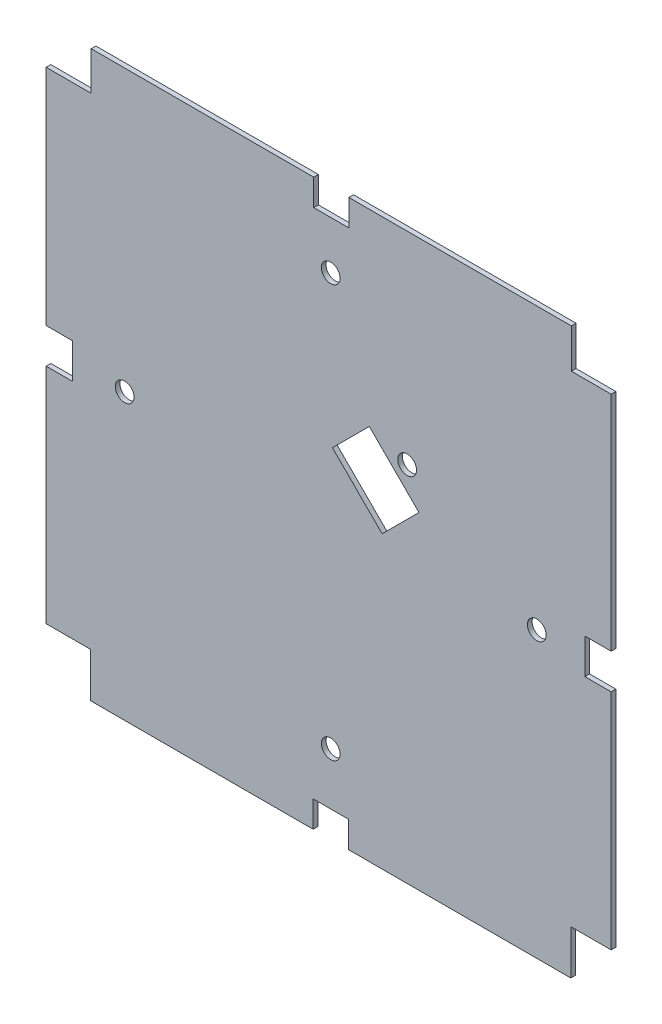
SolidWorks part; units mm, degrees
ref_plane "Front Plane" through (0, 0, 0) normal (0, 0, 1) x (1, 0, 0)
ref_plane "Top Plane" through (0, 0, 0) normal (0, 1, 0) x (1, 0, 0)
ref_plane "Right Plane" through (0, 0, 0) normal (1, 0, 0) x (0, 0, -1)
sketch "Sketch1" plane through (0, 0, 0) normal (0, 0, 1) x (1, 0, 0)
  line L1 (-67.0283, 35.647) -> (29.4717, 35.647)
  line L2 (-67.0283, 35.647) -> (-67.0283, -60.853)
  line L3 (-67.0283, -60.853) -> (29.4717, -60.853)
  line L4 (29.4717, 35.647) -> (29.4717, -60.853)
  line L5 (-67.0283, 35.647) -> (-59.3283, 35.647)
  line L6 (-67.0283, 35.647) -> (-67.0283, 29.047)
  line L7 (-67.0283, 29.047) -> (-59.3283, 29.047)
  line L8 (-59.3283, 35.647) -> (-59.3283, 29.047)
  line L21 (-67.0283, -9.153) -> (-62.5283, -9.153)
  line L22 (-67.0283, -9.153) -> (-67.0283, -15.153)
  line L23 (-67.0283, -15.153) -> (-62.5283, -15.153)
  line L24 (-62.5283, -9.153) -> (-62.5283, -15.153)
  line L25 (29.4717, 35.647) -> (22.6717, 35.647)
  line L26 (29.4717, 35.647) -> (29.4717, 28.947)
  line L27 (29.4717, 28.947) -> (22.6717, 28.947)
  line L28 (22.6717, 35.647) -> (22.6717, 28.947)
  line L29 (29.4717, -15.073) -> (24.9717, -15.073)
  line L30 (29.4717, -15.073) -> (29.4717, -9.073)
  line L31 (29.4717, -9.073) -> (24.9717, -9.073)
  line L32 (24.9717, -15.073) -> (24.9717, -9.073)
  line L33 (29.4717, -60.853) -> (22.5717, -60.853)
  line L34 (29.4717, -60.853) -> (29.4717, -53.253)
  line L35 (29.4717, -53.253) -> (22.5717, -53.253)
  line L36 (22.5717, -60.853) -> (22.5717, -53.253)
  line L37 (-67.0283, -60.853) -> (-59.4283, -60.853)
  line L38 (-67.0283, -60.853) -> (-67.0283, -53.253)
  line L39 (-67.0283, -53.253) -> (-59.4283, -53.253)
  line L40 (-59.4283, -60.853) -> (-59.4283, -53.253)
  line L42 (-21.3283, 35.647) -> (-15.3283, 35.647)
  line L43 (-21.3283, 35.647) -> (-21.3283, 31.147)
  line L44 (-21.3283, 31.147) -> (-15.3283, 31.147)
  line L45 (-15.3283, 35.647) -> (-15.3283, 31.147)
  line L47 (-21.4283, -60.853) -> (-15.4283, -60.853)
  line L48 (-21.4283, -60.853) -> (-21.4283, -56.353)
  line L49 (-21.4283, -56.353) -> (-15.4283, -56.353)
  line L50 (-15.4283, -60.853) -> (-15.4283, -56.353)
  circle A0 centre (16.7687, -12.2528) radius 1.6
  circle A1 centre (-18.4281, 22.944) radius 1.6
  circle A2 centre (-18.4281, -47.4496) radius 1.6
  circle A3 centre (-53.625, -12.2528) radius 1.6
  circle A4 centre (-5.3709, 1.097) radius 1.6
  circle A5 centre (16.7687, -12.2528) radius 1.7 construction
  circle A6 centre (-53.625, -12.2528) radius 1.7 construction
  circle A7 centre (-18.4281, 22.944) radius 1.7 construction
  circle A8 centre (-18.4281, -47.4496) radius 1.7 construction
  circle A10 centre (-5.3709, 1.097) radius 1.6 construction
  dimension "D17" = 3.2
  dimension "D19" = 3.2
  dimension "D20" = 3.2
  dimension "D21" = 3.2
  dimension "D27" = 3.2
  dimension "D16" = 0
  dimension "D22" = 0
  dimension "D23" = 0
  dimension "D1" = 96.5
  dimension "D2" = 96.5
  dimension "D3" = 4.5
  dimension "D4" = 7.7
  dimension "D5" = 6.6
  dimension "D6" = 6
  dimension "D7" = 45.7
  dimension "D8" = 7.6
  dimension "D9" = 7.6
  dimension "D10" = 6.9
  dimension "D11" = 7.6
  dimension "D12" = 6
  dimension "D13" = 4.5
  dimension "D14" = 6.7
  dimension "D15" = 6.8
  dimension "D18" = 0
  dimension "D25" = 0
  dimension "D28" = 4.5
  dimension "D29" = 6
  dimension "D30" = 45.7
  dimension "D33" = 4.5
  dimension "D34" = 6
  dimension "D35" = 45.6
extrude "Boss-Extrude1" add sketch "Sketch1" along normal blind 0.8 contours L40 L3 L36 L35 L4 L29 L32 L31 L27 L28 L1 L8 L7 L2 L21 L24 L23 L39 A4 A3 A2 A1 A0
sketch "Sketch2" plane through (0, 0, 0.8) normal (0, 0, 1) x (1, 0, 0)
  line L0 (-11.8377, 3.523) -> (-3.3524, -4.9623)
  line L1 (-11.8377, 3.523) -> (-18.1309, -2.7703)
  line L2 (-3.3524, -4.9623) -> (-9.6457, -11.2556)
  line L3 (-18.1309, -2.7703) -> (-9.6457, -11.2556)
  line L4 (-16.4205, -1.0599) -> (-7.9353, -9.5452)
  line L5 (-5.0361, -6.646) -> (-13.5214, 1.8392)
  line L6 (-59.4283, -60.853) -> (-21.4283, -60.853) construction
  line L7 (-67.0283, -15.153) -> (-67.0283, -53.253) construction
  point P10 (-10.7283, -3.853)
  dimension "D1" = 45
  dimension "D2" = 8.9
  dimension "D3" = 12
  dimension "D4" = 4.1
  dimension "D5" = 2.05
  dimension "D6" = 6
  dimension "D7" = 56.3
  dimension "D8" = 57
extrude "Cut-Extrude1" cut sketch "Sketch2" against normal blind 0.8 contours L4 L1 L3 L2 | L2 L5 L1 L4 | L5 L2 L0 L1
equation "\"D5@Sketch2\"=\"D4@Sketch2\"/2"
equation "\"D6@Sketch2\"=\"D3@Sketch2\"/2"
